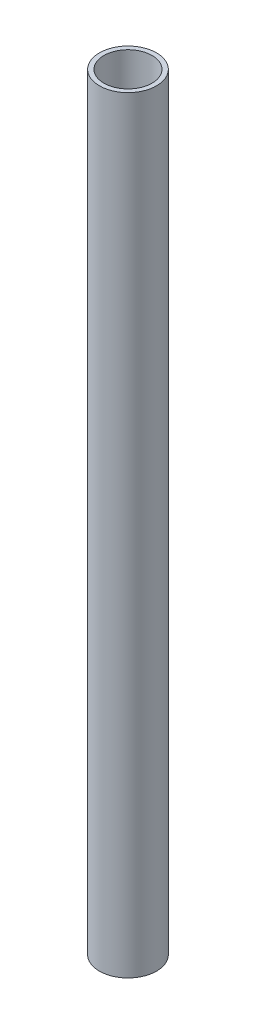
SolidWorks part; units mm, degrees
ref_plane "Front Plane" through (0, 0, 0) normal (0, 0, 1) x (1, 0, 0)
ref_plane "Top Plane" through (0, 0, 0) normal (0, 1, 0) x (1, 0, 0)
ref_plane "Right Plane" through (0, 0, 0) normal (1, 0, 0) x (0, 0, -1)
sketch "Sketch1" plane through (0, 0, 0) normal (0, 1, 0) x (1, 0, 0)
  circle A0 centre (0, 0) radius 19
  dimension "D1" = 38
extrude "Extrude-Thin1" add sketch "Sketch1" along normal mid plane 510 thin thin type one direction reverse wall 3
cosmetic thread "Cosmetic Thread1" parameters "D1"=14, "D2"=36
